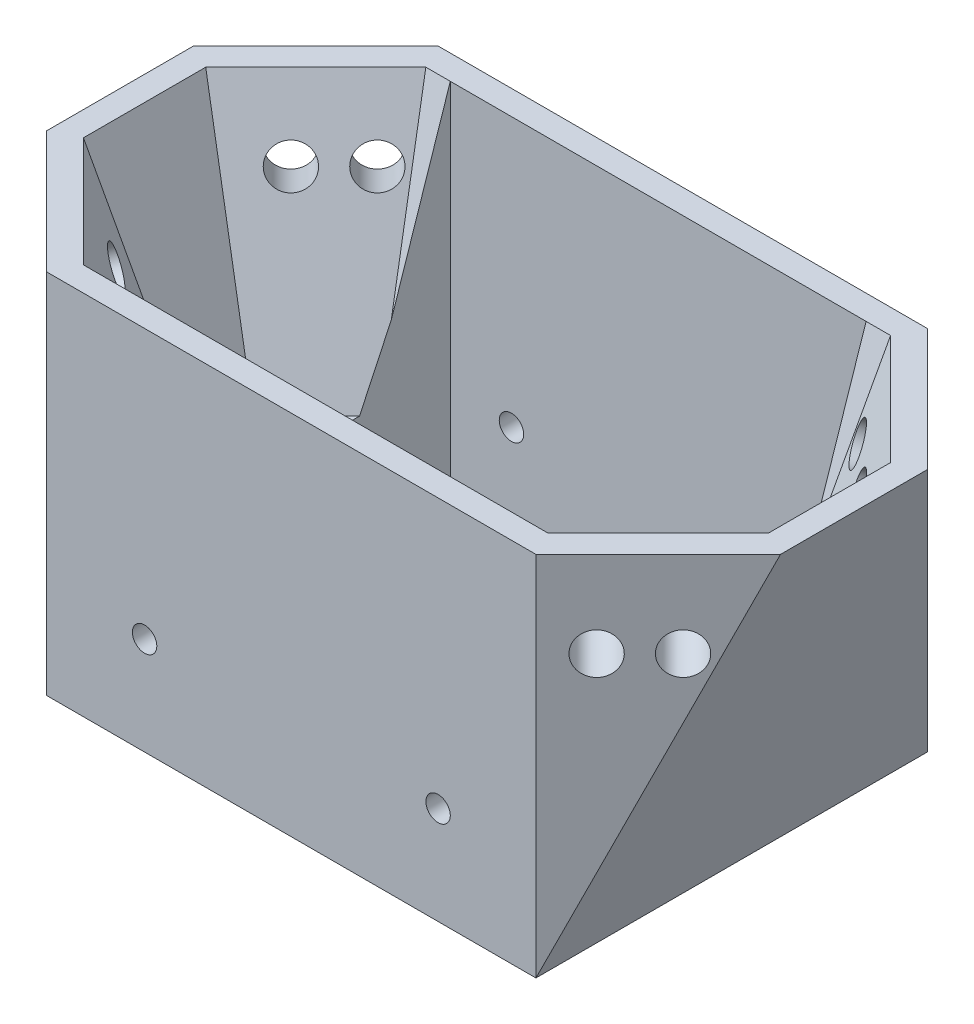
SolidWorks part; units mm, degrees
other "Markup1"
sketch "Sketch11" plane through (150, 150, 80) normal (0.263, 0.9633, 0.0541) x (0.2016, 0, -0.9795)
ref_plane "Front Plane" through (0, 0, 0) normal (0, 0, 1) x (1, 0, 0)
ref_plane "Top Plane" through (0, 0, 0) normal (0, 1, 0) x (1, 0, 0)
ref_plane "Right Plane" through (0, 0, 0) normal (1, 0, 0) x (0, 0, -1)
sketch "Sketch1" plane through (0, 0, 0) normal (0, 1, 0) x (1, 0, 0)
  line L0 (-150, 30) -> (-100, 80)
  line L1 (-100, 80) -> (100, 80)
  line L2 (100, 80) -> (150, 30)
  line L3 (150, 30) -> (150, -30)
  line L4 (150, -30) -> (100, -80)
  line L5 (100, -80) -> (-100, -80)
  line L6 (-100, -80) -> (-150, -30)
  line L7 (-150, -30) -> (-150, 30)
  dimension "D1" = 300
  dimension "D2" = 50
  dimension "D3" = 50
  dimension "D4" = 200
  dimension "D5" = 200
  dimension "D6" = 60
  dimension "D7" = 60
  dimension "D8" = 150
  dimension "D9" = 160
  dimension "D10" = 80
extrude "Boss-Extrude1" add sketch "Sketch1" along normal blind 150
sketch "Sketch2" plane through (0, 0, 0) normal (0, 0, 1) x (1, 0, 0)
  line L0 (-150, 150) -> (-100, 0)
  line L1 (-100, 0) -> (-150, 0)
  line L2 (-150, 0) -> (-150, 150)
  line L3 (100, 0) -> (150, 150)
  line L4 (150, 150) -> (150, 0)
  line L5 (150, 0) -> (100, 0)
extrude "Cut-Extrude1" cut sketch "Sketch2" against normal through all both and the other way through all
sketch "Sketch3" plane through (0, 0, 0) normal (0, 0, 1) x (1, 0, 0)
  line L0 (-85, 200) -> (85, 200)
  line L1 (85, 200) -> (85, 10)
  line L3 (85, 10) -> (-85, 10)
  line L5 (-85, 10) -> (-85, 200)
  line L6 (-100, 0) -> (100, 0) construction
  dimension "D1" = 170
  dimension "D2" = 85
  dimension "D3" = 170
  dimension "D4" = 10
  dimension "D5" = 200
extrude "Cut-Extrude2" cut sketch "Sketch3" against normal mid plane 140
sketch "Sketch4" plane through (0, 150, 0) normal (0, 1, 0) x (1, 0, 0)
  line L0 (-140, -25) -> (-125, -40)
  line L1 (-125, -40) -> (-95, -70)
  line L2 (-95, -70) -> (95, -70)
  line L3 (95, -70) -> (140, -25)
  line L4 (140, -25) -> (140, 25)
  line L5 (140, 25) -> (95, 70)
  line L6 (95, 70) -> (-95, 70)
  line L7 (-95, 70) -> (-140, 25)
  line L8 (-140, 25) -> (-140, -25)
  line L9 (100, 80) -> (-100, 80) construction
  line L10 (-150, 30) -> (-150, -30) construction
  line L11 (-100, 80) -> (-150, 30) construction
  line L13 (-150, -30) -> (-100, -80) construction
  line L14 (100, -80) -> (150, -30) construction
  line L15 (150, 30) -> (100, 80) construction
  dimension "D1" = 10
  dimension "D2" = 150
  dimension "D3" = 10
  dimension "D4" = 290
  dimension "D5" = 190
  dimension "D6" = 190
  dimension "D7" = 45
extrude "Cut-Extrude3" cut sketch "Sketch4" against normal blind 100 draft 18.43
sketch "Sketch7" plane through (0, 0, 80) normal (0, 0, 1) x (1, 0, 0)
  line L0 (-100, 150) -> (-100, 0) construction
  line L1 (-100, 0) -> (100, 0) construction
  circle A0 centre (-60, 40) radius 5
  circle A1 centre (60, 40) radius 5
  dimension "D1" = 10
  dimension "D2" = 10
  dimension "D3" = 40
  dimension "D4" = 160
  dimension "D5" = 40
  dimension "D6" = 40
extrude "Cut-Extrude5" cut sketch "Sketch7" against normal through all
sketch "Sketch9" plane through (0, 10, 0) normal (0, 1, 0) x (1, 0, 0)
  line L0 (-85, 70) -> (85, 70) construction
  line L5 (65, 5) -> (75, 5)
  line L6 (-85, -70) -> (85, -70) construction
  line L7 (-25, -35) -> (-20, -35)
  line L8 (-25, -35) -> (-25, -50)
  line L9 (-25, -50) -> (-20, -50)
  line L10 (-20, -35) -> (-20, -50)
  line L11 (85, 70) -> (85, -70) construction
  line L22 (65, 5) -> (65, 2)
  line L23 (65, 2) -> (75, 2)
  line L24 (75, 5) -> (75, 2)
  point P12 (-22.5, -50)
  dimension "D1" = 105
  dimension "D2" = 3
  dimension "D3" = 10
  dimension "D4" = 10
  dimension "D5" = 5
  dimension "D6" = 65
  dimension "D7" = 15
  dimension "D8" = 20
extrude "Boss-Extrude2" add sketch "Sketch9" along normal blind 15
sketch "Sketch10" plane through (-42.4418, -20.0015, 42.4418) normal (0.6708, 0.3161, -0.6708) x (-0.6068, -0.286, -0.7416)
  line L0 (23.5191, 195.3693) -> (-37.1603, 176.1858) construction
  line L1 (-4.6063, 106.3883) -> (-37.1603, 176.1858) construction
  circle A0 centre (-14.7551, 151.8056) radius 8
  circle A1 centre (9.0821, 159.3416) radius 8
  dimension "D1" = 16
  dimension "D2" = 16
  dimension "D3" = 25
  dimension "D4" = 30
  dimension "D5" = 30
  dimension "D6" = 10
extrude "Cut-Extrude6" cut sketch "Sketch10" against normal blind 40
mirror "Mirror1" about plane through (0, 0, 0) normal (1, 0, 0) of "Cut-Extrude6" second plane through (0, 0, 0) second plane normal (0, 0, 1)
